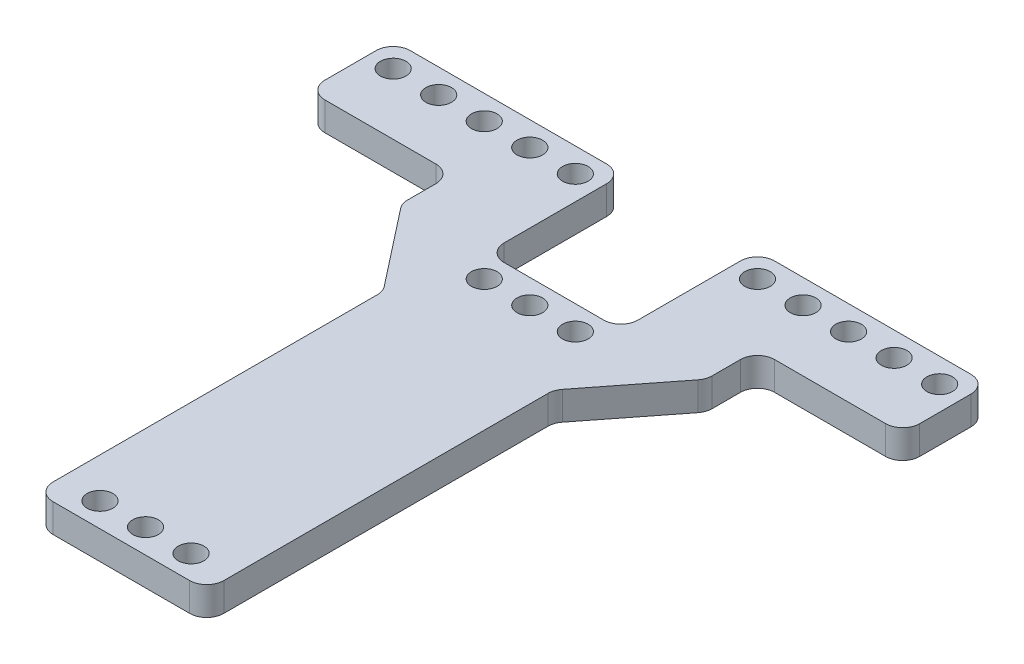
SolidWorks part; units mm, degrees
ref_plane "前视基准面" through (0, 0, 0) normal (0, 0, 1) x (1, 0, 0)
ref_plane "上视基准面" through (0, 0, 0) normal (0, 1, 0) x (1, 0, 0)
ref_plane "右视基准面" through (0, 0, 0) normal (1, 0, 0) x (0, 0, -1)
sketch "草图2" plane through (0, 0, 0) normal (0, 1, 0) x (1, 0, 0)
  line L0 (-48, 45.75) -> (-40, 45.75) construction
  line L1 (-52.25, 50) -> (52.25, 50)
  line L2 (-52.25, 50) -> (-52.25, 35)
  line L4 (52.25, 50) -> (52.25, 35)
  line L5 (-52.25, 50) -> (52.25, -50) construction
  line L6 (-52.25, -50) -> (52.25, 50) construction
  line L7 (0, 50) -> (0, -50) construction
  line L8 (-26.75, 35) -> (-52.25, 35)
  line L9 (-11.75, 26) -> (11.75, 26)
  line L10 (-11.75, 26) -> (-11.75, 50)
  line L11 (-11.75, 50) -> (11.75, 50)
  line L12 (11.75, 26) -> (11.75, 50)
  line L13 (-11.75, 26) -> (11.75, 50) construction
  line L14 (-11.75, 50) -> (11.75, 26) construction
  line L15 (-26.75, 35) -> (-26.75, 26)
  line L17 (26.75, 35) -> (52.25, 35)
  line L21 (-52.25, 35) -> (-52.25, -50) construction
  line L23 (-52.25, -50) -> (52.25, -50) construction
  line L25 (52.25, 35) -> (52.25, -50) construction
  line L27 (-26.75, 26) -> (-26.75, 11) construction
  line L29 (26.75, 35) -> (26.75, 26)
  line L34 (-26.75, 26) -> (-15, 11)
  line L35 (11.495, 11) -> (15, 11) construction
  line L36 (-15, 11) -> (-15, -50)
  line L37 (-15, -50) -> (15, -50)
  line L38 (15, 11) -> (15, -50)
  line L39 (26.75, 26) -> (15, 11)
  line L40 (-15, 11) -> (-11.495, 11) construction
  line L41 (-11.495, 11) -> (0, 11) construction
  line L42 (0, 11) -> (11.495, 11) construction
  circle A0 centre (-48, 45.75) radius 2.25
  circle A1 centre (-40, 45.75) radius 2.25
  circle A2 centre (-32, 45.75) radius 2.25
  circle A3 centre (-24, 45.75) radius 2.25
  circle A4 centre (-16, 45.75) radius 2.25
  circle A5 centre (48, 45.75) radius 2.25
  circle A6 centre (40, 45.75) radius 2.25
  circle A7 centre (32, 45.75) radius 2.25
  circle A8 centre (24, 45.75) radius 2.25
  circle A9 centre (16, 45.75) radius 2.25
  circle A10 centre (-8, 21.75) radius 2.25
  circle A11 centre (0, 21.75) radius 2.25
  circle A13 centre (8, 21.75) radius 2.25
  circle A14 centre (-8, -45.75) radius 2.25
  circle A15 centre (0, -45.75) radius 2.25
  circle A16 centre (8, -45.75) radius 2.25
  point P0 (0, 0)
  point P20 (0, 38)
  point P55 (0, -50)
  dimension "D3" = 4.5
  dimension "D4" = 4.25
  dimension "D10" = 4.5
  dimension "D11" = 24
  dimension "D12" = 4.5
  dimension "D13" = 8
  dimension "D1" = 104.5
  dimension "D2" = 100
  dimension "D5" = 4.25
  dimension "D7" = 8
  dimension "D8" = 4.25
  dimension "D9" = 4.25
  dimension "D14" = 15
  dimension "D15" = 15
  dimension "D16" = 15
  dimension "D17" = 30
  dimension "D18" = 15
  dimension "D19" = 2
  dimension "D20" = 4.25
  dimension "D6" = 5
extrude "凸台-拉伸1" add sketch "草图2" along normal blind 5
fillet "圆角1" radius 3 16 edges at (-11.75, 2.5, -50) (-11.75, 2.5, -26) (11.75, 2.5, -26) (11.75, 2.5, -50) (52.25, 2.5, -50) (52.25, 2.5, -35) (26.75, 2.5, -35) (26.75, 2.5, -26) (15, 2.5, -11) (15, 2.5, 50) (-15, 2.5, 50) (-15, 2.5, -11) (-26.75, 2.5, -26) (-26.75, 2.5, -35) (-52.25, 2.5, -35) (-52.25, 2.5, -50)
